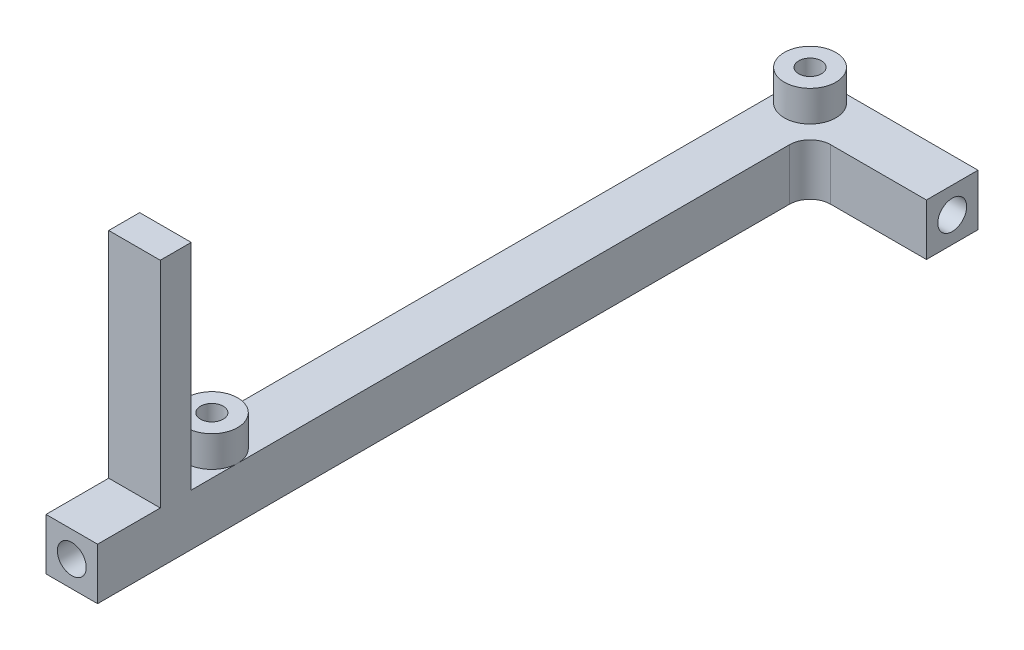
SolidWorks part; units mm, degrees
ref_plane "Front Plane" through (0, 0, 0) normal (0, 0, 1) x (1, 0, 0)
ref_plane "Top Plane" through (0, 0, 0) normal (0, 1, 0) x (1, 0, 0)
ref_plane "Right Plane" through (0, 0, 0) normal (1, 0, 0) x (0, 0, -1)
sketch "Sketch1" plane through (0, 0, 0) normal (0, 0, 1) x (1, 0, 0)
  line L1 (-2.5, 2.5) -> (2.5, 2.5)
  line L2 (-2.5, 2.5) -> (-2.5, -2.5)
  line L3 (-2.5, -2.5) -> (2.5, -2.5)
  line L4 (2.5, 2.5) -> (2.5, -2.5)
  line L5 (-2.5, 2.5) -> (2.5, -2.5) construction
  line L6 (-2.5, -2.5) -> (2.5, 2.5) construction
  point P0 (0, 0)
  dimension "D1" = 5
extrude "Boss-Extrude1" add sketch "Sketch1" along normal blind 74.08
sketch "Sketch2" plane through (0, 0, 74.08) normal (0, 0, 1) x (1, 0, 0)
  circle A0 centre (0, 0) radius 1.4
  dimension "D1" = 2.8
extrude "Cut-Extrude1" cut sketch "Sketch2" against normal blind 10
sketch "Sketch3" plane through (2.5, 0, 0) normal (1, 0, 0) x (0, 0, -1)
  line L0 (-74.08, -2.5) -> (0, -2.5) construction
  line L1 (0, 2.5) -> (-5, 2.5)
  line L2 (0, 2.5) -> (0, -2.5)
  line L3 (0, -2.5) -> (-5, -2.5)
  line L4 (-5, 2.5) -> (-5, -2.5)
  dimension "D1" = 5
extrude "Boss-Extrude2" add sketch "Sketch3" along normal blind 11.28
sketch "Sketch4" plane through (13.78, 0, 0) normal (1, 0, 0) x (0, 0, -1)
  line L0 (0, 2.5) -> (-5, -2.5) construction
  circle A0 centre (-2.5, 0) radius 1.4
  dimension "D1" = 2.8
extrude "Cut-Extrude2" cut sketch "Sketch4" against normal blind 10
sketch "Sketch5" plane through (0, 2.5, 0) normal (0, 1, 0) x (1, 0, 0)
  line L0 (0, 0) -> (0, -74.08) construction
  line L1 (2.5, -74.08) -> (-2.5, -74.08) construction
  line L2 (2.5, -5) -> (-2.5, 0) construction
  line L5 (2.5, -74.08) -> (2.5, -5) construction
  line L6 (-2.5, -74.08) -> (-2.5, 0) construction
  circle A0 centre (0, -60.5) radius 2.5
  circle A1 centre (0, -2.5) radius 2.5
  circle A2 centre (0, -60.5) radius 1.1
  circle A3 centre (0, -2.5) radius 1.1
  dimension "D2" = 2.2
  dimension "D1" = 13.58
extrude "Boss-Extrude3" add sketch "Sketch5" along normal blind 3
fillet "Fillet1" radius 2 2 edges at (-2.5, 0, 0) (2.5, 0, 5)
sketch "Sketch7" plane through (0, 2.5, 0) normal (0, 1, 0) x (1, 0, 0)
  line L0 (-2.5, -74.08) -> (-2.5, -60.5) construction
  line L1 (-2.5, -65) -> (2.5, -65)
  line L2 (-2.5, -65) -> (-2.5, -68)
  line L3 (-2.5, -68) -> (2.5, -68)
  line L4 (2.5, -65) -> (2.5, -68)
  line L5 (2.5, -74.08) -> (2.5, -60.5) construction
  line L6 (-2.5, -63) -> (2.5, -63) construction
  circle A0 centre (0, -60.5) radius 2.5 construction
  dimension "D1" = 3
  dimension "D2" = 2
extrude "Boss-Extrude4" add sketch "Sketch7" along normal blind 20.8
